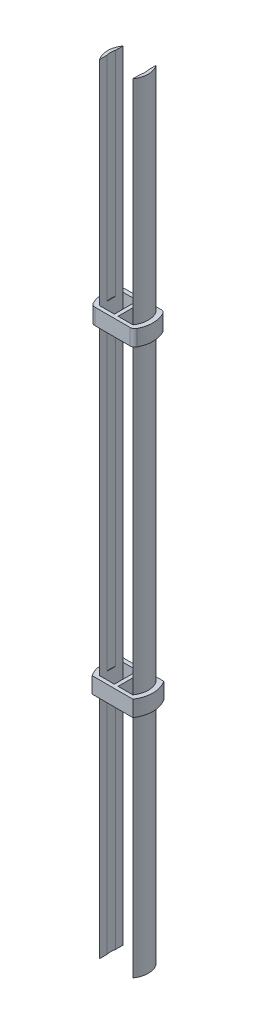
SolidWorks part; units mm, degrees
material "6061 Alloy"
ref_plane "Front Plane" through (0, 0, 0) normal (0, 0, 1) x (1, 0, 0)
ref_plane "Top Plane" through (0, 0, 0) normal (0, 1, 0) x (1, 0, 0)
ref_plane "Right Plane" through (0, 0, 0) normal (1, 0, 0) x (0, 0, -1)
sketch "Sketch1" plane through (0, 0, 0) normal (0, 1, 0) x (1, 0, 0)
  circle A0 centre (0, 0) radius 10.75
  circle A1 centre (0, 0) radius 12.7
  dimension "D1" = 21.5
extrude "Boss-Extrude1" add sketch "Sketch1" along normal blind 510
sketch "Sketch2" plane through (0, 510, 0) normal (0, 1, 0) x (1, 0, 0)
  line L0 (0, 12.7) -> (0, 6.7) construction
  line L1 (0, 6.7) -> (8.4067, 6.7) construction
  line L2 (8.4067, 6.7) -> (10.4067, 6.7) construction
  line L3 (10.4067, 24.4874) -> (10.4067, -11.0874)
  line L4 (0, 6.7) -> (-8.4067, 6.7) construction
  line L5 (-8.4067, 6.7) -> (-10.4067, 6.7) construction
  line L6 (-10.4067, 23.6494) -> (-10.4067, -10.2494)
  line L7 (10.4067, 24.4874) -> (-10.4067, 23.6494)
  line L8 (10.4067, -11.0874) -> (10.4067, -15.2224)
  line L9 (10.4067, -15.2224) -> (-10.4067, -15.2224)
  line L10 (-10.4067, -15.2224) -> (-10.4067, -10.2494)
  circle A0 centre (0, 0) radius 12.7 construction
  circle A1 centre (0, 0) radius 10.75 construction
  point P13 (10.4067, 6.7)
  point P18 (-10.4067, 6.7)
extrude "Cut-Extrude1" cut sketch "Sketch2" against normal blind 510
sketch "Sketch3" plane through (0, 0, 0) normal (1, 0, 0) x (0, 0, -1)
  line L0 (-7.2795, 0) -> (-7.2795, 12)
  line L1 (-7.2795, 510) -> (-7.2795, 0) construction
  line L2 (-7.2795, 12) -> (11.5511, 12)
  line L3 (11.5511, 12) -> (11.5511, 0)
  line L4 (11.5511, 0) -> (-7.2795, 0)
  line L5 (-7.2795, 510) -> (-7.2795, 498)
  line L6 (-7.2795, 498) -> (9.7051, 498)
  line L7 (9.7051, 498) -> (9.7051, 510)
  line L8 (9.7051, 510) -> (-7.2795, 510)
extrude "Cut-Extrude2" cut sketch "Sketch3" against normal blind 19 and the other way blind 16
ref_plane "Plane1" through (0, 260, 0) normal (0, 1, 0) x (1, 0, 0)
ref_plane "Plane2" through (0, 355, 0) normal (0, 1, 0) x (1, 0, 0)
sketch "Sketch5" plane through (0, 355, 0) normal (0, 1, 0) x (1, 0, 0)
  line L0 (-10.4067, 7.2795) -> (-10.4067, -7.2795)
  line L5 (12.7, 9.7205) -> (-12.7, 9.7205)
  line L6 (-10.4067, 7.2795) -> (-1.15, 7.2795)
  line L7 (10.4067, 7.2795) -> (10.4067, -7.2795)
  line L9 (-12.7, -9.5795) -> (12.7, -9.5795)
  line L11 (10.4067, -7.2795) -> (1.15, -7.2795)
  line L12 (-1.15, -7.2795) -> (-10.4067, -7.2795)
  line L13 (1.15, 7.2795) -> (1.15, -7.2795)
  line L14 (-1.15, 7.2795) -> (-1.15, -7.2795)
  line L15 (1.15, 7.2795) -> (10.4067, 7.2795)
  arc A12 (-12.7, -9.5795) -> (-12.7, 9.7205) centre (1.4427, 0.0705) cw
  arc A13 (12.7, 9.7205) -> (12.7, -9.5795) centre (-1.8044, 0.0705) cw
  point P18 (0, 7.2795)
extrude "Boss-Extrude2" add sketch "Sketch5" along normal blind 10
fillet "Fillet1" radius 3 4 edges at (-12.7, 360, 9.5795) (12.7, 360, 9.5795) (12.7, 360, -9.7205) (-12.7, 360, -9.7205)
mirror "Mirror1" about plane through (0, 260, 0) normal (0, 1, 0) of "Boss-Extrude2"
